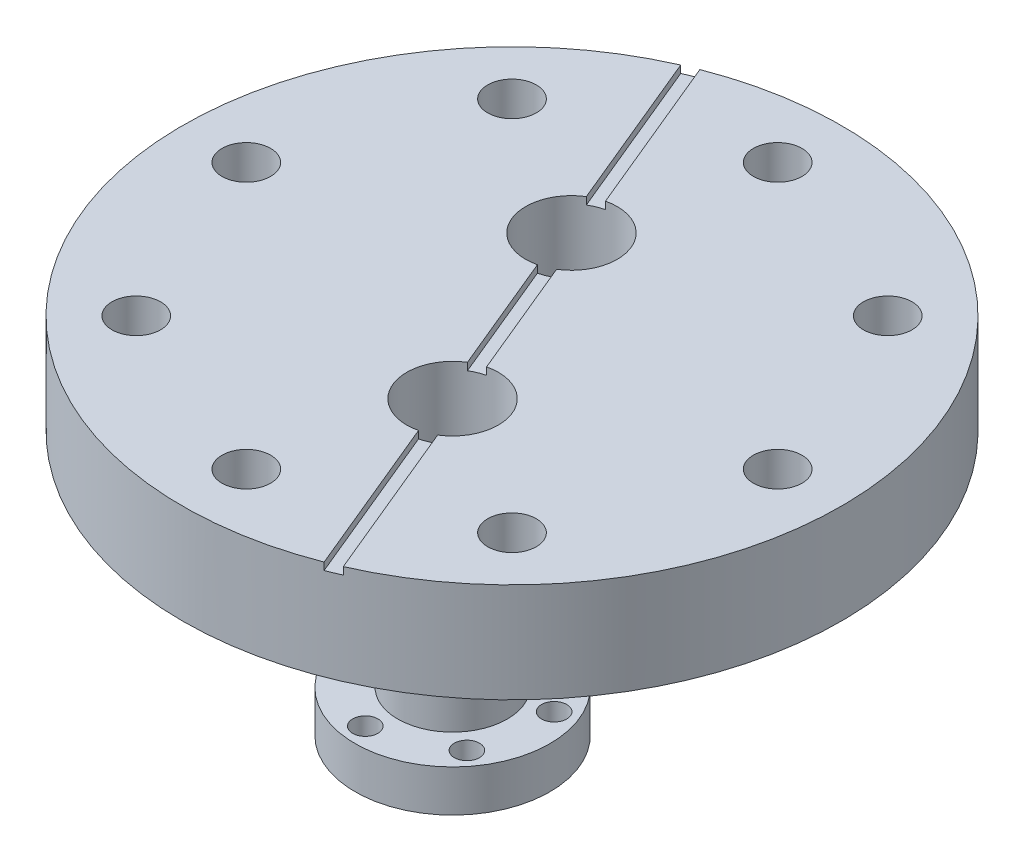
SolidWorks part; units mm, degrees
ref_plane "Front Plane" through (0, 0, 0) normal (0, 0, 1) x (1, 0, 0)
ref_plane "Top Plane" through (0, 0, 0) normal (0, 1, 0) x (1, 0, 0)
ref_plane "Right Plane" through (0, 0, 0) normal (1, 0, 0) x (0, 0, -1)
sketch "Sketch1" plane through (0, 0, 0) normal (0, 1, 0) x (1, 0, 0)
  circle A0 centre (0, 0) radius 57.15
  dimension "D1" = 114.3
extrude "Extrude1" add sketch "Sketch1" along normal blind 17.272
sketch "Sketch3" plane through (0, 0, 0) normal (0, -1, 0) x (1, 0, 0)
  circle A0 centre (0, 46.0756) radius 4.2164
  dimension "D1" = 8.4328
  dimension "D2" = 46.0756
extrude "Extrude2" cut sketch "Sketch3" against normal through all
pattern_circular "CirPattern1" count 8 over 360 about axis through (0, 0, 0) along (0, 1, 0) of "Extrude2"
sketch "Sketch5" plane through (0, 0, 0) normal (0, -1, 0) x (1, 0, 0)
  line L0 (0, 0) -> (27.6852, 66.838) construction
  line L1 (0, 0) -> (0, 46.0756) construction
  circle A0 centre (7.2901, 17.5999) radius 7.9375
  circle A1 centre (7.2901, 17.5999) radius 9.4996
  dimension "D2" = 15.875
  dimension "D3" = 18.9992
  dimension "D1" = 22.5
  dimension "D4" = 19.05
extrude "Extrude3" add sketch "Sketch5" along normal blind 33.3375
sketch "Sketch6" plane through (0, -33.3375, 0) normal (0, -1, 0) x (1, 0, 0)
  circle A0 centre (7.2901, 17.5999) radius 7.9375
  circle A1 centre (7.2901, 17.5999) radius 16.891
  dimension "D1" = 33.782
extrude "Extrude4" add sketch "Sketch6" against normal blind 7.239
sketch "Sketch7" plane through (0, -33.3375, 0) normal (0, -1, 0) x (1, 0, 0)
  line L0 (7.2901, 17.5999) -> (0, 0) construction
  line L1 (7.2901, 17.5999) -> (-12.2066, 2.6395) construction
  circle A0 centre (-3.4102, 9.3893) radius 2.1844
  dimension "D3" = 4.3688
  dimension "D1" = 30
  dimension "D2" = 13.4874
extrude "Extrude5" cut sketch "Sketch7" against normal up to next
pattern_circular "CirPattern2" count 6 over 360 about axis through (7.2901, 0, 17.5999) along (0, 1, 0) of "Extrude5"
sketch "Sketch8" plane through (0, -33.3375, 0) normal (0, -1, 0) x (1, 0, 0)
  circle A0 centre (7.2901, 17.5999) radius 7.9375
extrude "Extrude6" cut sketch "Sketch8" against normal through all
sketch "Sketch9" plane through (0, 0, 0) normal (0, -1, 0) x (1, 0, 0)
  line L0 (0, 0) -> (-25.2111, -60.865) construction
  line L1 (0, 0) -> (0, -27.3134) construction
  circle A0 centre (-7.2901, -17.5999) radius 16.891
  circle A1 centre (-7.2901, -17.5999) radius 7.9375
  dimension "D2" = 33.782
  dimension "D3" = 15.875
  dimension "D1" = 22.5
  dimension "D4" = 19.05
extrude "Extrude7" add sketch "Sketch9" along normal blind 7.239
sketch "Sketch11" plane through (0, -7.239, 0) normal (0, -1, 0) x (1, 0, 0)
  circle A0 centre (-7.2901, -17.5999) radius 7.9375
extrude "Extrude8" cut sketch "Sketch11" against normal through all
sketch "Sketch12" plane through (0, -7.239, 0) normal (0, -1, 0) x (1, 0, 0)
  line L0 (-7.2901, -17.5999) -> (0, 0) construction
  line L1 (-7.2901, -17.5999) -> (14.1049, -1.1829) construction
  circle A0 centre (3.4102, -9.3893) radius 2.1844
  dimension "D2" = 4.3688
  dimension "D1" = 30
  dimension "D3" = 13.4874
extrude "Extrude9" cut sketch "Sketch12" against normal blind 7.239
pattern_circular "CirPattern3" count 6 over 360 about axis through (-7.2901, 0, -17.5999) along (0, 1, 0) of "Extrude9"
sketch "Sketch13" plane through (0, 17.272, 0) normal (0, 1, 0) x (1, 0, 0)
  line L0 (-7.2901, 17.5999) -> (7.2901, -17.5999) construction
  line L1 (-24.156, 61.6363) -> (-26.5026, 60.6643)
  line L2 (-26.5026, 60.6643) -> (25.6606, -65.2689)
  line L3 (25.6606, -65.2689) -> (28.0073, -64.2969)
  line L4 (-24.156, 61.6363) -> (28.0073, -64.2969)
  point P10 (26.8339, -64.7829)
  point P11 (-25.3293, 61.1503)
  dimension "D1" = 2.54
extrude "Extrude10" cut sketch "Sketch13" against normal blind 1.27
